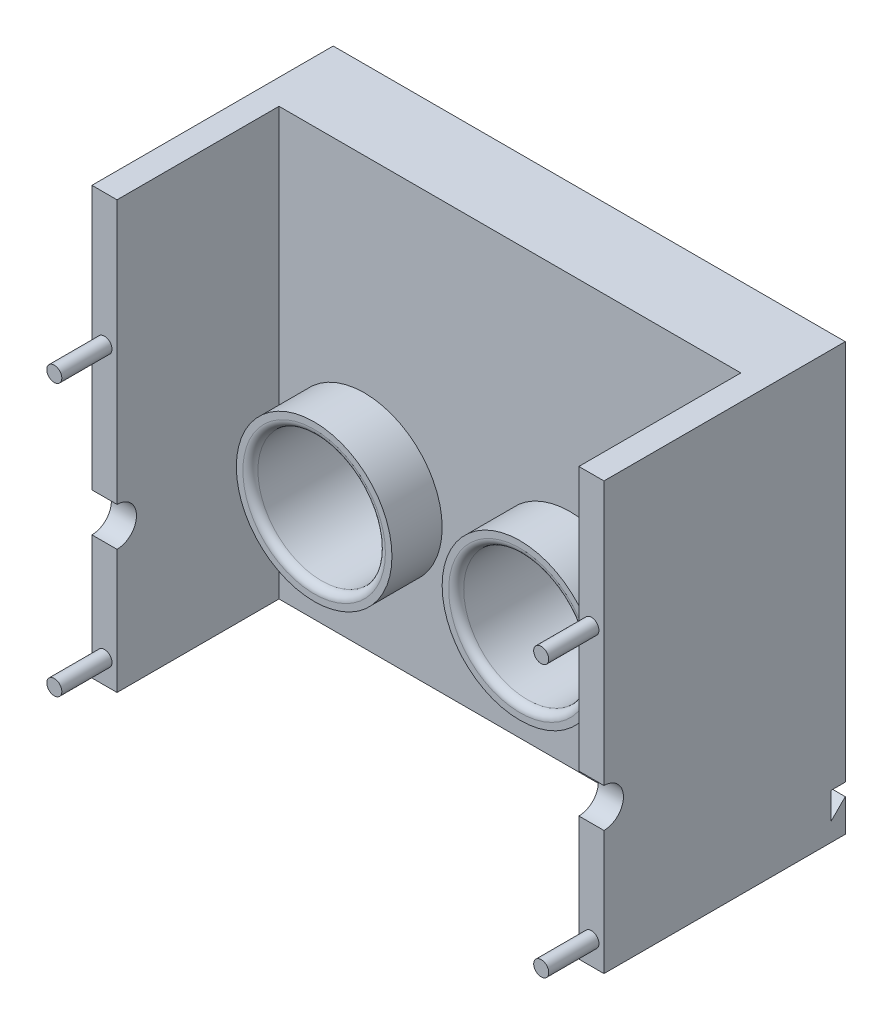
SolidWorks part; units mm, degrees
ref_plane "Front Plane" through (0, 0, 0) normal (0, 0, 1) x (1, 0, 0)
ref_plane "Top Plane" through (0, 0, 0) normal (0, 1, 0) x (1, 0, 0)
ref_plane "Right Plane" through (0, 0, 0) normal (1, 0, 0) x (0, 0, -1)
sketch "Sketch2" plane through (0, 0, 0) normal (0, 1, 0) x (1, 0, 0)
  line L1 (-46, -32.265) -> (46, -32.265)
  line L2 (-46, -32.265) -> (-46, 32.265)
  line L3 (-46, 32.265) -> (46, 32.265)
  line L4 (46, -32.265) -> (46, 32.265)
  line L5 (-46, -32.265) -> (46, 32.265) construction
  line L6 (-46, 32.265) -> (46, -32.265) construction
  line L11 (-12.2964, -8.6248) -> (31.4076, 22.0297) construction
  line L12 (-23.9905, 11.7) -> (23.9905, -11.7) construction
  line L17 (51, -48.065) -> (-51, -48.065)
  line L18 (51, -48.065) -> (51, 48.065)
  line L19 (51, 48.065) -> (-51, 48.065)
  line L20 (-51, -48.065) -> (-51, 48.065)
  line L21 (51, -48.065) -> (-51, 48.065) construction
  line L22 (51, 48.065) -> (-51, -48.065) construction
  point P0 (0, 0)
  point P6 (0, 0)
  point P11 (0, 0)
  point P12 (0, 0)
  dimension "D1" = 92
  dimension "D2" = 96.13
  dimension "D3" = 102
  dimension "D4" = 64.53
extrude "Boss-Extrude1" add sketch "Sketch2" along normal blind 85
sketch "Sketch8" plane through (0, 0, 48.065) normal (0, 0, 1) x (1, 0, 0)
  line L0 (-51, 85) -> (-51, 0) construction
  circle A0 centre (-31, 31.7) radius 10.25
  circle A2 centre (29, 31.7) radius 10.25
  dimension "D1" = 20.5
  dimension "D3" = 20.5
  dimension "D2" = 20
  dimension "D4" = 60
extrude "Cut-Extrude7" cut sketch "Sketch8" against normal blind 20
sketch "Sketch9" plane through (0, 0, -48.065) normal (0, 0, -1) x (-1, 0, 0)
  line L1 (51, 85) -> (51, 0) construction
  line L2 (-51, 0) -> (51, 0) construction
  circle A0 centre (-12, 28.575) radius 12.7
  circle A1 centre (29, 28.575) radius 12.7
  dimension "D1" = 25.4
  dimension "D3" = 25.4
  dimension "D2" = 63
  dimension "D4" = 22
  dimension "D5" = 28.575
  dimension "D6" = 28.575
extrude "Cut-Extrude8" cut sketch "Sketch9" against normal blind 20
sketch "Sketch10" plane through (-51, 0, 0) normal (-1, 0, 0) x (0, 0, 1)
  circle A0 centre (0, 28.575) radius 3.875
  dimension "D1" = 7.75
  dimension "D2" = 28.575
extrude "Cut-Extrude9" cut sketch "Sketch10" against normal through all
sketch "Sketch11" plane through (-51, 0, 0) normal (-1, 0, 0) x (0, 0, 1)
  line L0 (0, 85) -> (0, -6.6181) construction
  line L1 (-48.065, 85) -> (48.065, 85) construction
  line L2 (0, 85) -> (0, 0)
  line L3 (-48.065, 0) -> (48.065, 0) construction
  line L4 (48.065, 85) -> (48.065, 0) construction
  line L5 (0, 85) -> (48.065, 85)
  line L6 (0, 0) -> (48.065, 0)
  line L7 (48.065, 85) -> (48.065, 0)
extrude "Cut-Extrude10" cut sketch "Sketch11" against normal through all
sketch "Sketch14" plane through (0, 0, 0) normal (0, 0, 1) x (1, 0, 0)
  line L0 (0, 70.8572) -> (0, -12.1382) construction
  line L1 (-74.4766, 31.7) -> (73.019, 31.7) construction
  line L2 (-48.5, 85) -> (-48.5, 32.45) construction
  line L3 (-46, 85) -> (-51, 85) construction
  line L4 (-46, 32.45) -> (-51, 32.45) construction
  circle A0 centre (-48.5, 58.725) radius 1.5
  circle A1 centre (-48.5, 4.675) radius 1.5
  circle A2 centre (48.5, 4.675) radius 1.5
  circle A3 centre (48.5, 58.725) radius 1.5
  dimension "D1" = 3
  dimension "D2" = 3
extrude "Boss-Extrude2" add sketch "Sketch14" along normal blind 10
sketch "Sketch15" plane through (0, 0, -32.265) normal (0, 0, 1) x (1, 0, 0)
  circle A9 centre (12, 28.575) radius 15.5
  circle A10 centre (-29, 28.575) radius 15.5
  circle A11 centre (-29, 28.575) radius 12.7
  circle A12 centre (12, 28.575) radius 12.7
  dimension "D1" = 31
  dimension "D2" = 31
extrude "Boss-Extrude3" add sketch "Sketch15" along normal blind 10
fillet "Fillet1" radius 1.5 2 edges at (24.7, 28.575, -22.265) (-16.3, 28.575, -22.265)
sketch "Sketch16" plane through (-51, 0, 0) normal (-1, 0, 0) x (0, 0, 1)
  line L0 (-48.065, 6.5) -> (-45.2366, 3.6716)
  line L1 (-48.065, 85) -> (-48.065, 0) construction
  line L2 (-45.2366, 3.6716) -> (-45.2366, 9)
  line L3 (-45.2366, 9) -> (-48.065, 9)
  line L4 (-48.065, 6.5) -> (-48.065, 9)
  dimension "D1" = 6.5
  dimension "D2" = 9
  dimension "D3" = 4
  dimension "D4" = 45
extrude "Cut-Extrude11" cut sketch "Sketch16" against normal through all
